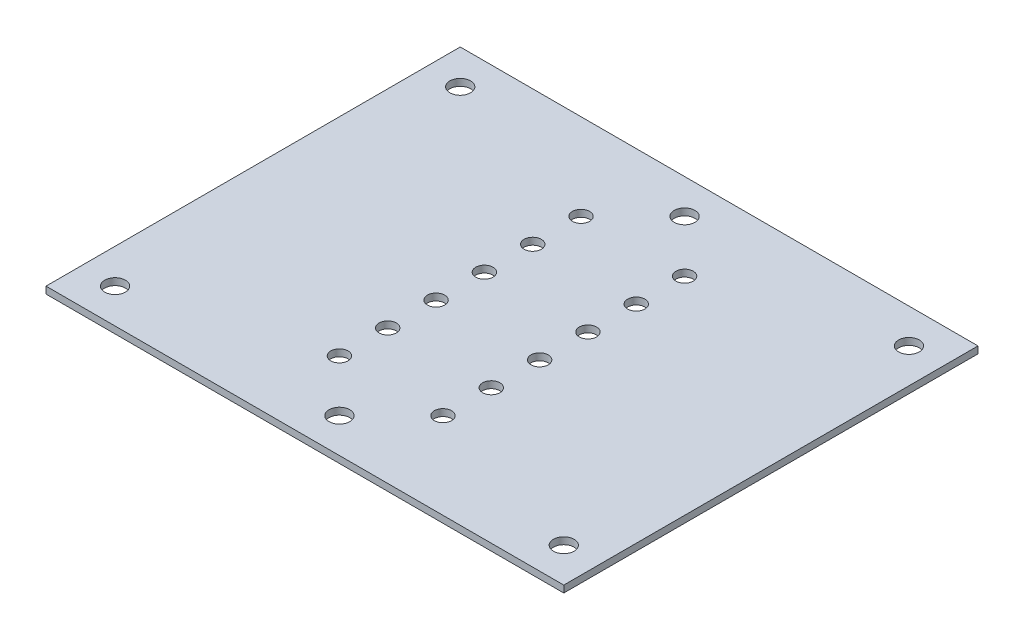
SolidWorks part; units mm, degrees
ref_plane "前视基准面" through (0, 0, 0) normal (0, 0, 1) x (1, 0, 0)
ref_plane "上视基准面" through (0, 0, 0) normal (0, 1, 0) x (1, 0, 0)
ref_plane "右视基准面" through (0, 0, 0) normal (1, 0, 0) x (0, 0, -1)
sketch "草图1" plane through (0, 0, 0) normal (0, 1, 0) x (1, 0, 0)
  line L1 (-37.5, -30) -> (37.5, -30)
  line L2 (-37.5, -30) -> (-37.5, 30)
  line L3 (-37.5, 30) -> (37.5, 30)
  line L4 (37.5, -30) -> (37.5, 30)
  line L5 (-37.5, -30) -> (37.5, 30) construction
  line L6 (-37.5, 30) -> (37.5, -30) construction
  point P0 (0, 0)
  dimension "D1" = 75
  dimension "D2" = 60
extrude "凸台-拉伸1" add sketch "草图1" along normal blind 1
sketch "草图2" plane through (0, 0, 0) normal (0, 1, 0) x (1, 0, 0)
  line L0 (-37.5, 30) -> (-37.5, -30) construction
  line L1 (37.5, 30) -> (-37.5, 30) construction
  circle A0 centre (-7.5, 17.5) radius 1.25
  circle A1 centre (7.5, 17.5) radius 1.25
  circle A2 centre (7.5, 10.5) radius 1.25
  circle A3 centre (7.5, 3.5) radius 1.25
  circle A4 centre (7.5, -3.5) radius 1.25
  circle A5 centre (7.5, -10.5) radius 1.25
  circle A6 centre (7.5, -17.5) radius 1.25
  circle A7 centre (-7.5, 10.5) radius 1.25
  circle A8 centre (-7.5, 3.5) radius 1.25
  circle A9 centre (-7.5, -3.5) radius 1.25
  circle A10 centre (-7.5, -10.5) radius 1.25
  circle A11 centre (-7.5, -17.5) radius 1.25
  dimension "D1" = 30
  dimension "D2" = 2.5
  dimension "D5" = 12.5
  dimension "D6" = 15
  dimension "D3" = 2
  dimension "D4" = 6
extrude "切除-拉伸1" cut sketch "草图2" along normal through all
sketch "草图3" plane through (0, 0, 0) normal (0, 1, 0) x (1, 0, 0)
  line L0 (-37.5, 30) -> (-37.5, -30) construction
  line L1 (30, 30) -> (30, 15.9014) construction
  line L3 (37.5, 30) -> (-37.5, 30) construction
  line L4 (0, 30) -> (0, 15.9014) construction
  line L5 (0, 0) -> (-16.574, 0) construction
  circle A0 centre (-32.5, 25) radius 1.5
  circle A2 centre (32.5, -25) radius 1.5
  circle A3 centre (-32.5, -25) radius 1.5
  circle A5 centre (32.5, 25) radius 1.5
  circle A7 centre (-2.5, 25) radius 1.5 [skipped]
  circle A8 centre (0, -25) radius 1.5
  circle A9 centre (0, 25) radius 1.5
  dimension "D1" = 3
  dimension "D6" = 3
  dimension "D2" = 5
  dimension "D3" = 5
  dimension "D4" = 2
  dimension "D5" = 2
extrude "切除-拉伸2" cut sketch "草图3" along normal through all
